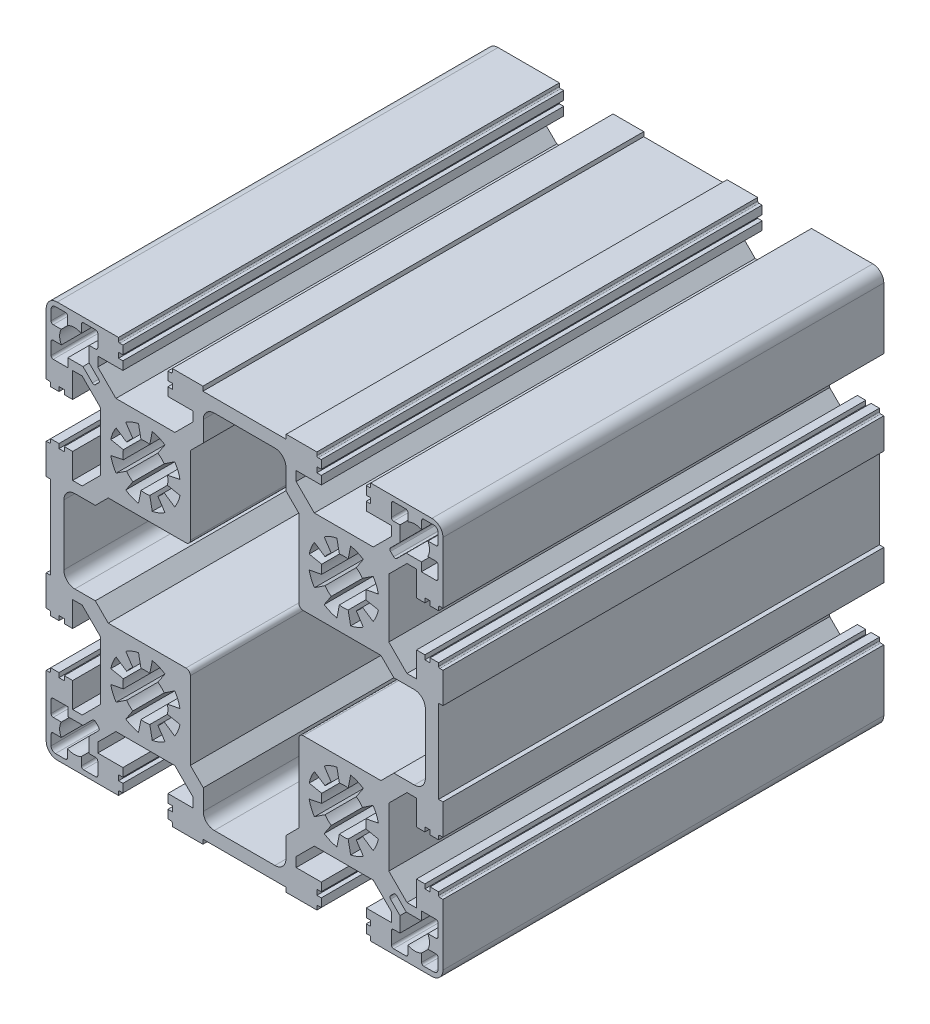
SolidWorks part; units mm, degrees
ref_plane "前视基准面" through (0, 0, 0) normal (0, 0, 1) x (1, 0, 0)
ref_plane "上视基准面" through (0, 0, 0) normal (0, 1, 0) x (1, 0, 0)
ref_plane "右视基准面" through (0, 0, 0) normal (1, 0, 0) x (0, 0, -1)
sketch "草图1" plane through (0, 0, 0) normal (0, 0, 1) x (1, 0, 0)
  line L0 (-27.5688, 44.5458) -> (-41.4688, 44.5458)
  line L1 (-43.9688, 42.0458) -> (-43.9688, 28.1458)
  line L2 (-26.5688, 38.5458) -> (-32.2688, 38.5458)
  line L3 (-37.9688, 32.8458) -> (-37.9688, 27.1458)
  line L4 (-26.5688, 43.5458) -> (-27.2688, 43.5458)
  line L5 (-27.5688, 43.8458) -> (-27.5688, 44.5458)
  line L6 (-43.9688, 28.1458) -> (-43.2688, 28.1458)
  line L7 (-42.9688, 27.8458) -> (-42.9688, 27.1458)
  line L8 (-37.9688, 32.8458) -> (-35.8043, 32.8458)
  line L9 (-41.0688, 28.1458) -> (-39.8688, 28.1458)
  line L10 (-42.9688, 27.1458) -> (-41.0688, 27.1458)
  line L11 (-39.8688, 27.1458) -> (-37.9688, 27.1458)
  line L12 (-32.2688, 38.5458) -> (-32.2688, 36.3813)
  line L13 (-27.5688, 41.6458) -> (-27.5688, 40.4458)
  line L14 (-26.5688, 43.5458) -> (-26.5688, 41.6458)
  line L15 (-26.5688, 40.4458) -> (-26.5688, 38.5458)
  line L16 (-26.5688, 40.4458) -> (-27.5688, 40.4458)
  line L17 (-26.5688, 41.6458) -> (-27.5688, 41.6458)
  line L19 (-39.8688, 27.1458) -> (-39.8688, 28.1458)
  line L20 (-41.0688, 27.1458) -> (-41.0688, 28.1458)
  line L21 (-16.3688, 38.5458) -> (-10.6688, 38.5458)
  line L22 (-16.3688, 43.5458) -> (-15.6688, 43.5458)
  line L23 (-15.3688, 43.8458) -> (-15.3688, 44.5458)
  line L24 (-10.6688, 38.5458) -> (-10.6688, 36.3813)
  line L25 (-15.3688, 41.6458) -> (-15.3688, 40.4458)
  line L26 (-16.3688, 40.4458) -> (-15.3688, 40.4458)
  line L27 (-16.3688, 41.6458) -> (-15.3688, 41.6458)
  line L28 (-16.3688, 43.5458) -> (-16.3688, 41.6458)
  line L29 (-16.3688, 40.4458) -> (-16.3688, 38.5458)
  line L30 (-37.9688, 11.2458) -> (-37.9688, 16.9458)
  line L31 (-43.9688, 15.9458) -> (-43.2688, 15.9458)
  line L32 (-42.9688, 16.2458) -> (-42.9688, 16.9458)
  line L33 (-37.9688, 11.2458) -> (-35.8043, 11.2458)
  line L34 (-41.0688, 15.9458) -> (-39.8688, 15.9458)
  line L35 (-42.9688, 16.9458) -> (-41.0688, 16.9458)
  line L36 (-39.8688, 16.9458) -> (-37.9688, 16.9458)
  line L38 (-39.8688, 16.9458) -> (-39.8688, 15.9458)
  line L39 (-41.0688, 16.9458) -> (-41.0688, 15.9458)
  line L40 (-31.6888, 28.7303) -> (-31.6888, 15.3613)
  line L41 (-14.7843, 32.2658) -> (-28.1532, 32.2658)
  line L42 (-25.9133, 15.394) -> (-24.3022, 17.8053)
  line L43 (-23.0295, 14.1995) -> (-22.4637, 17.0438)
  line L44 (-19.9081, 14.1995) -> (-20.4738, 17.0438)
  line L45 (-17.0242, 15.394) -> (-18.6354, 17.8053)
  line L46 (-14.817, 17.6012) -> (-17.2283, 19.2124)
  line L47 (-13.6225, 20.4851) -> (-16.4668, 21.0508)
  line L48 (-13.6225, 23.6065) -> (-16.4668, 23.0408)
  line L49 (-14.817, 26.4904) -> (-17.2283, 24.8792)
  line L50 (-17.0242, 28.6975) -> (-18.6354, 26.2863)
  line L51 (-19.9081, 29.8921) -> (-20.4738, 27.0478)
  line L52 (-23.0295, 29.8921) -> (-22.4637, 27.0478)
  line L53 (-25.9133, 28.6975) -> (-24.3022, 26.2863)
  line L54 (-28.1205, 26.4904) -> (-25.7093, 24.8792)
  line L55 (-29.3151, 23.6065) -> (-26.4708, 23.0408)
  line L56 (-29.3151, 20.4851) -> (-26.4708, 21.0508)
  line L57 (-28.1205, 17.6012) -> (-25.7093, 19.2124)
  line L58 (-32.2688, 36.3813) -> (-28.1532, 32.2658)
  line L59 (-35.8043, 32.8458) -> (-31.6888, 28.7303)
  line L60 (-10.6688, 36.3813) -> (-14.7843, 32.2658)
  line L61 (-35.8043, 11.2458) -> (-31.6888, 15.3613)
  line L63 (-42.8688, 42.4458) -> (-42.8688, 40.1458)
  line L64 (-42.3688, 39.6458) -> (-40.5642, 39.6458)
  line L65 (-34.2188, 39.6458) -> (-32.7688, 39.6458)
  line L66 (-32.2688, 40.1458) -> (-32.2688, 42.9458)
  line L67 (-32.7688, 43.4458) -> (-35.5088, 43.4458)
  line L68 (-36.0088, 42.9458) -> (-36.0088, 41.1104)
  line L70 (-39.1288, 41.1104) -> (-39.1288, 42.9458)
  line L71 (-39.6288, 43.4458) -> (-41.8688, 43.4458)
  line L72 (-34.2188, 36.21) -> (-34.2188, 39.6458)
  line L73 (-35.633, 34.7958) -> (-33.4896, 32.6524)
  line L74 (-34.2188, 36.21) -> (-32.0754, 34.0666)
  line L75 (-32.7825, 32.6524) -> (-32.0754, 33.3595)
  line L76 (-35.633, 34.7958) -> (-39.0688, 34.7958)
  line L77 (-40.5334, 36.5858) -> (-42.3688, 36.5858)
  line L79 (-42.8688, 36.0858) -> (-42.8688, 33.3458)
  line L80 (-42.3688, 32.8458) -> (-39.0688, 32.8458)
  line L81 (-39.0688, 34.7958) -> (-39.0688, 32.8458)
  line L99 (18.4312, 38.5458) -> (12.7312, 38.5458)
  line L100 (18.4312, 43.5458) -> (17.7312, 43.5458)
  line L101 (17.4312, 43.8458) -> (17.4312, 44.5458)
  line L102 (12.7312, 38.5458) -> (12.7312, 36.3813)
  line L103 (17.4312, 41.6458) -> (17.4312, 40.4458)
  line L104 (18.4312, 43.5458) -> (18.4312, 41.6458)
  line L105 (18.4312, 40.4458) -> (18.4312, 38.5458)
  line L106 (18.4312, 40.4458) -> (17.4312, 40.4458)
  line L107 (18.4312, 41.6458) -> (17.4312, 41.6458)
  line L108 (29.6312, 44.5458) -> (43.5312, 44.5458)
  line L109 (46.0312, 42.0458) -> (46.0312, 28.1458)
  line L110 (28.6312, 38.5458) -> (34.3312, 38.5458)
  line L111 (40.0312, 32.8458) -> (40.0312, 27.1458)
  line L112 (28.6312, 43.5458) -> (29.3312, 43.5458)
  line L113 (29.6312, 43.8458) -> (29.6312, 44.5458)
  line L114 (46.0312, 28.1458) -> (45.3312, 28.1458)
  line L115 (45.0312, 27.8458) -> (45.0312, 27.1458)
  line L116 (40.0312, 32.8458) -> (37.8668, 32.8458)
  line L117 (43.1312, 28.1458) -> (41.9312, 28.1458)
  line L118 (45.0312, 27.1458) -> (43.1312, 27.1458)
  line L119 (41.9312, 27.1458) -> (40.0312, 27.1458)
  line L120 (34.3312, 38.5458) -> (34.3312, 36.3813)
  line L121 (29.6312, 41.6458) -> (29.6312, 40.4458)
  line L122 (28.6312, 40.4458) -> (29.6312, 40.4458)
  line L123 (28.6312, 41.6458) -> (29.6312, 41.6458)
  line L125 (41.9312, 27.1458) -> (41.9312, 28.1458)
  line L126 (43.1312, 27.1458) -> (43.1312, 28.1458)
  line L127 (28.6312, 43.5458) -> (28.6312, 41.6458)
  line L128 (28.6312, 40.4458) -> (28.6312, 38.5458)
  line L129 (40.0312, 11.2458) -> (40.0312, 16.9458)
  line L130 (46.0312, 15.9458) -> (45.3312, 15.9458)
  line L131 (45.0312, 16.2458) -> (45.0312, 16.9458)
  line L132 (40.0312, 11.2458) -> (37.8668, 11.2458)
  line L133 (43.1312, 15.9458) -> (41.9312, 15.9458)
  line L134 (45.0312, 16.9458) -> (43.1312, 16.9458)
  line L135 (41.9312, 16.9458) -> (40.0312, 16.9458)
  line L137 (41.9312, 16.9458) -> (41.9312, 15.9458)
  line L138 (43.1312, 16.9458) -> (43.1312, 15.9458)
  line L139 (33.7512, 15.3613) -> (33.7512, 28.7303)
  line L140 (30.2157, 32.2658) -> (16.8468, 32.2658)
  line L141 (19.0867, 15.394) -> (20.6978, 17.8053)
  line L142 (21.9705, 14.1995) -> (22.5363, 17.0438)
  line L143 (25.0919, 14.1995) -> (24.5262, 17.0438)
  line L144 (27.9758, 15.394) -> (26.3646, 17.8053)
  line L145 (30.183, 17.6012) -> (27.7717, 19.2124)
  line L146 (31.3775, 20.4851) -> (28.5332, 21.0508)
  line L147 (31.3775, 23.6065) -> (28.5332, 23.0408)
  line L148 (30.183, 26.4904) -> (27.7717, 24.8792)
  line L149 (27.9758, 28.6975) -> (26.3646, 26.2863)
  line L150 (25.0919, 29.8921) -> (24.5262, 27.0478)
  line L151 (21.9705, 29.8921) -> (22.5363, 27.0478)
  line L152 (19.0867, 28.6975) -> (20.6978, 26.2863)
  line L153 (16.8795, 26.4904) -> (19.2907, 24.8792)
  line L154 (15.6849, 23.6065) -> (18.5292, 23.0408)
  line L155 (15.6849, 20.4851) -> (18.5292, 21.0508)
  line L156 (16.8795, 17.6012) -> (19.2907, 19.2124)
  line L157 (12.7312, 36.3813) -> (16.8468, 32.2658)
  line L158 (34.3312, 36.3813) -> (30.2157, 32.2658)
  line L159 (37.8668, 32.8458) -> (33.7512, 28.7303)
  line L160 (37.8668, 11.2458) -> (33.7512, 15.3613)
  line L161 (36.2812, 39.6458) -> (34.8312, 39.6458)
  line L162 (34.3312, 40.1458) -> (34.3312, 42.9458)
  line L163 (34.8312, 43.4458) -> (37.5712, 43.4458)
  line L164 (38.0712, 42.9458) -> (38.0712, 41.1104)
  line L165 (41.1912, 41.1104) -> (41.1912, 42.9458)
  line L166 (41.6912, 43.4458) -> (43.9312, 43.4458)
  line L167 (44.9312, 42.4458) -> (44.9312, 40.1458)
  line L168 (44.4312, 39.6458) -> (42.6266, 39.6458)
  line L169 (42.5958, 36.5858) -> (44.4312, 36.5858)
  line L170 (44.9312, 36.0858) -> (44.9312, 33.3458)
  line L171 (44.4312, 32.8458) -> (41.1312, 32.8458)
  line L172 (41.1312, 32.8458) -> (41.1312, 34.7958)
  line L173 (41.1312, 34.7958) -> (37.6954, 34.7958)
  line L174 (37.6954, 34.7958) -> (35.552, 32.6524)
  line L175 (34.8449, 32.6524) -> (34.1378, 33.3595)
  line L176 (34.1378, 34.0666) -> (36.2812, 36.21)
  line L177 (36.2812, 36.21) -> (36.2812, 39.6458)
  line L178 (-15.3688, 44.5458) -> (-8.4188, 44.5458)
  line L179 (-8.4188, 43.5458) -> (10.4812, 43.5458)
  line L180 (-8.3394, 33.4074) -> (-8.3394, 38.0458)
  line L181 (-5.8394, 40.5458) -> (7.9019, 40.5458)
  line L182 (10.4019, 38.0458) -> (10.4019, 33.4074)
  line L183 (-8.3394, 33.4074) -> (-11.2688, 30.478)
  line L184 (17.4312, 44.5458) -> (10.4812, 44.5458)
  line L185 (10.4019, 33.4074) -> (13.3312, 30.478)
  line L186 (10.4812, 43.5458) -> (10.4812, 44.5458)
  line L187 (-8.4188, 43.5458) -> (-8.4188, 44.5458)
  line L188 (-11.2688, 30.478) -> (-11.2688, 12.8458)
  line L189 (13.3312, 30.478) -> (13.3312, 12.8458)
  line L190 (-27.5688, -45.4542) -> (-41.4688, -45.4542)
  line L191 (-43.9688, -42.9542) -> (-43.9688, -29.0542)
  line L192 (-26.5688, -39.4542) -> (-32.2688, -39.4542)
  line L193 (-37.9688, -33.7542) -> (-37.9688, -28.0542)
  line L194 (-26.5688, -44.4542) -> (-27.2688, -44.4542)
  line L195 (-27.5688, -44.7542) -> (-27.5688, -45.4542)
  line L196 (-43.9688, -29.0542) -> (-43.2688, -29.0542)
  line L197 (-42.9688, -28.7542) -> (-42.9688, -28.0542)
  line L198 (-37.9688, -33.7542) -> (-35.8043, -33.7542)
  line L199 (-41.0688, -29.0542) -> (-39.8688, -29.0542)
  line L200 (-42.9688, -28.0542) -> (-41.0688, -28.0542)
  line L201 (-39.8688, -28.0542) -> (-37.9688, -28.0542)
  line L202 (-32.2688, -39.4542) -> (-32.2688, -37.2897)
  line L203 (-27.5688, -42.5542) -> (-27.5688, -41.3542)
  line L204 (-26.5688, -44.4542) -> (-26.5688, -42.5542)
  line L205 (-26.5688, -41.3542) -> (-26.5688, -39.4542)
  line L206 (-26.5688, -41.3542) -> (-27.5688, -41.3542)
  line L207 (-26.5688, -42.5542) -> (-27.5688, -42.5542)
  line L209 (-39.8688, -28.0542) -> (-39.8688, -29.0542)
  line L210 (-41.0688, -28.0542) -> (-41.0688, -29.0542)
  line L211 (-16.3688, -39.4542) -> (-10.6688, -39.4542)
  line L212 (-16.3688, -44.4542) -> (-15.6688, -44.4542)
  line L213 (-15.3688, -44.7542) -> (-15.3688, -45.4542)
  line L214 (-10.6688, -39.4542) -> (-10.6688, -37.2897)
  line L215 (-15.3688, -42.5542) -> (-15.3688, -41.3542)
  line L216 (-16.3688, -41.3542) -> (-15.3688, -41.3542)
  line L217 (-16.3688, -42.5542) -> (-15.3688, -42.5542)
  line L218 (-16.3688, -44.4542) -> (-16.3688, -42.5542)
  line L219 (-16.3688, -41.3542) -> (-16.3688, -39.4542)
  line L220 (-37.9688, -12.1542) -> (-37.9688, -17.8542)
  line L221 (-43.9688, -16.8542) -> (-43.2688, -16.8542)
  line L222 (-42.9688, -17.1542) -> (-42.9688, -17.8542)
  line L223 (-37.9688, -12.1542) -> (-35.8043, -12.1542)
  line L224 (-41.0688, -16.8542) -> (-39.8688, -16.8542)
  line L225 (-42.9688, -17.8542) -> (-41.0688, -17.8542)
  line L226 (-39.8688, -17.8542) -> (-37.9688, -17.8542)
  line L228 (-39.8688, -17.8542) -> (-39.8688, -16.8542)
  line L229 (-41.0688, -17.8542) -> (-41.0688, -16.8542)
  line L230 (-31.6888, -29.6387) -> (-31.6888, -16.2697)
  line L231 (-14.7843, -33.1742) -> (-28.1532, -33.1742)
  line L232 (-25.9133, -16.3025) -> (-24.3022, -18.7137)
  line L233 (-23.0295, -15.1079) -> (-22.4637, -17.9522)
  line L234 (-19.9081, -15.1079) -> (-20.4738, -17.9522)
  line L235 (-17.0242, -16.3025) -> (-18.6354, -18.7137)
  line L236 (-14.817, -18.5096) -> (-17.2283, -20.1208)
  line L237 (-13.6225, -21.3935) -> (-16.4668, -21.9592)
  line L238 (-13.6225, -24.5149) -> (-16.4668, -23.9492)
  line L239 (-14.817, -27.3988) -> (-17.2283, -25.7876)
  line L240 (-17.0242, -29.606) -> (-18.6354, -27.1947)
  line L241 (-19.9081, -30.8005) -> (-20.4738, -27.9562)
  line L242 (-23.0295, -30.8005) -> (-22.4637, -27.9562)
  line L243 (-25.9133, -29.606) -> (-24.3022, -27.1947)
  line L244 (-28.1205, -27.3988) -> (-25.7093, -25.7876)
  line L245 (-29.3151, -24.5149) -> (-26.4708, -23.9492)
  line L246 (-29.3151, -21.3935) -> (-26.4708, -21.9592)
  line L247 (-28.1205, -18.5096) -> (-25.7093, -20.1208)
  line L248 (-32.2688, -37.2897) -> (-28.1532, -33.1742)
  line L249 (-35.8043, -33.7542) -> (-31.6888, -29.6387)
  line L250 (-10.6688, -37.2897) -> (-14.7843, -33.1742)
  line L251 (-35.8043, -12.1542) -> (-31.6888, -16.2697)
  line L253 (-42.8688, -43.3542) -> (-42.8688, -41.0542)
  line L254 (-42.3688, -40.5542) -> (-40.5642, -40.5542)
  line L255 (-34.2188, -40.5542) -> (-32.7688, -40.5542)
  line L256 (-32.2688, -41.0542) -> (-32.2688, -43.8542)
  line L257 (-32.7688, -44.3542) -> (-35.5088, -44.3542)
  line L258 (-36.0088, -43.8542) -> (-36.0088, -42.0188)
  line L260 (-39.1288, -42.0188) -> (-39.1288, -43.8542)
  line L261 (-39.6288, -44.3542) -> (-41.8688, -44.3542)
  line L262 (-34.2188, -37.1184) -> (-34.2188, -40.5542)
  line L263 (-35.633, -35.7042) -> (-33.4896, -33.5608)
  line L264 (-34.2188, -37.1184) -> (-32.0754, -34.975)
  line L265 (-32.7825, -33.5608) -> (-32.0754, -34.2679)
  line L266 (-35.633, -35.7042) -> (-39.0688, -35.7042)
  line L267 (-40.5334, -37.4942) -> (-42.3688, -37.4942)
  line L269 (-42.8688, -36.9942) -> (-42.8688, -34.2542)
  line L270 (-42.3688, -33.7542) -> (-39.0688, -33.7542)
  line L271 (-39.0688, -35.7042) -> (-39.0688, -33.7542)
  line L289 (18.4312, -39.4542) -> (12.7312, -39.4542)
  line L290 (18.4312, -44.4542) -> (17.7312, -44.4542)
  line L291 (17.4312, -44.7542) -> (17.4312, -45.4542)
  line L292 (12.7312, -39.4542) -> (12.7312, -37.2897)
  line L293 (17.4312, -42.5542) -> (17.4312, -41.3542)
  line L294 (18.4312, -44.4542) -> (18.4312, -42.5542)
  line L295 (18.4312, -41.3542) -> (18.4312, -39.4542)
  line L296 (18.4312, -41.3542) -> (17.4312, -41.3542)
  line L297 (18.4312, -42.5542) -> (17.4312, -42.5542)
  line L298 (29.6312, -45.4542) -> (43.5312, -45.4542)
  line L299 (46.0312, -42.9542) -> (46.0312, -29.0542)
  line L300 (28.6312, -39.4542) -> (34.3312, -39.4542)
  line L301 (40.0312, -33.7542) -> (40.0312, -28.0542)
  line L302 (28.6312, -44.4542) -> (29.3312, -44.4542)
  line L303 (29.6312, -44.7542) -> (29.6312, -45.4542)
  line L304 (46.0312, -29.0542) -> (45.3312, -29.0542)
  line L305 (45.0312, -28.7542) -> (45.0312, -28.0542)
  line L306 (40.0312, -33.7542) -> (37.8668, -33.7542)
  line L307 (43.1312, -29.0542) -> (41.9312, -29.0542)
  line L308 (45.0312, -28.0542) -> (43.1312, -28.0542)
  line L309 (41.9312, -28.0542) -> (40.0312, -28.0542)
  line L310 (34.3312, -39.4542) -> (34.3312, -37.2897)
  line L311 (29.6312, -42.5542) -> (29.6312, -41.3542)
  line L312 (28.6312, -41.3542) -> (29.6312, -41.3542)
  line L313 (28.6312, -42.5542) -> (29.6312, -42.5542)
  line L315 (41.9312, -28.0542) -> (41.9312, -29.0542)
  line L316 (43.1312, -28.0542) -> (43.1312, -29.0542)
  line L317 (28.6312, -44.4542) -> (28.6312, -42.5542)
  line L318 (28.6312, -41.3542) -> (28.6312, -39.4542)
  line L319 (40.0312, -12.1542) -> (40.0312, -17.8542)
  line L320 (46.0312, -16.8542) -> (45.3312, -16.8542)
  line L321 (45.0312, -17.1542) -> (45.0312, -17.8542)
  line L322 (40.0312, -12.1542) -> (37.8668, -12.1542)
  line L323 (43.1312, -16.8542) -> (41.9312, -16.8542)
  line L324 (45.0312, -17.8542) -> (43.1312, -17.8542)
  line L325 (41.9312, -17.8542) -> (40.0312, -17.8542)
  line L327 (41.9312, -17.8542) -> (41.9312, -16.8542)
  line L328 (43.1312, -17.8542) -> (43.1312, -16.8542)
  line L329 (33.7512, -16.2697) -> (33.7512, -29.6387)
  line L330 (30.2157, -33.1742) -> (16.8468, -33.1742)
  line L331 (19.0867, -16.3025) -> (20.6978, -18.7137)
  line L332 (21.9705, -15.1079) -> (22.5363, -17.9522)
  line L333 (25.0919, -15.1079) -> (24.5262, -17.9522)
  line L334 (27.9758, -16.3025) -> (26.3646, -18.7137)
  line L335 (30.183, -18.5096) -> (27.7717, -20.1208)
  line L336 (31.3775, -21.3935) -> (28.5332, -21.9592)
  line L337 (31.3775, -24.5149) -> (28.5332, -23.9492)
  line L338 (30.183, -27.3988) -> (27.7717, -25.7876)
  line L339 (27.9758, -29.606) -> (26.3646, -27.1947)
  line L340 (25.0919, -30.8005) -> (24.5262, -27.9562)
  line L341 (21.9705, -30.8005) -> (22.5363, -27.9562)
  line L342 (19.0867, -29.606) -> (20.6978, -27.1947)
  line L343 (16.8795, -27.3988) -> (19.2907, -25.7876)
  line L344 (15.6849, -24.5149) -> (18.5292, -23.9492)
  line L345 (15.6849, -21.3935) -> (18.5292, -21.9592)
  line L346 (16.8795, -18.5096) -> (19.2907, -20.1208)
  line L347 (12.7312, -37.2897) -> (16.8468, -33.1742)
  line L348 (34.3312, -37.2897) -> (30.2157, -33.1742)
  line L349 (37.8668, -33.7542) -> (33.7512, -29.6387)
  line L350 (37.8668, -12.1542) -> (33.7512, -16.2697)
  line L351 (36.2812, -40.5542) -> (34.8312, -40.5542)
  line L352 (34.3312, -41.0542) -> (34.3312, -43.8542)
  line L353 (34.8312, -44.3542) -> (37.5712, -44.3542)
  line L354 (38.0712, -43.8542) -> (38.0712, -42.0188)
  line L355 (41.1912, -42.0188) -> (41.1912, -43.8542)
  line L356 (41.6912, -44.3542) -> (43.9312, -44.3542)
  line L357 (44.9312, -43.3542) -> (44.9312, -41.0542)
  line L358 (44.4312, -40.5542) -> (42.6266, -40.5542)
  line L359 (42.5958, -37.4942) -> (44.4312, -37.4942)
  line L360 (44.9312, -36.9942) -> (44.9312, -34.2542)
  line L361 (44.4312, -33.7542) -> (41.1312, -33.7542)
  line L362 (41.1312, -33.7542) -> (41.1312, -35.7042)
  line L363 (41.1312, -35.7042) -> (37.6954, -35.7042)
  line L364 (37.6954, -35.7042) -> (35.552, -33.5608)
  line L365 (34.8449, -33.5608) -> (34.1378, -34.2679)
  line L366 (34.1378, -34.975) -> (36.2812, -37.1184)
  line L367 (36.2812, -37.1184) -> (36.2812, -40.5542)
  line L368 (-15.3688, -45.4542) -> (-8.4188, -45.4542)
  line L369 (-8.4188, -44.4542) -> (10.4812, -44.4542)
  line L370 (-8.3394, -34.3158) -> (-8.3394, -38.9542)
  line L371 (-5.8394, -41.4542) -> (7.9019, -41.4542)
  line L372 (10.4019, -38.9542) -> (10.4019, -34.3158)
  line L373 (-8.3394, -34.3158) -> (-11.2688, -31.3864)
  line L374 (17.4312, -45.4542) -> (10.4812, -45.4542)
  line L375 (10.4019, -34.3158) -> (13.3312, -31.3864)
  line L376 (10.4812, -44.4542) -> (10.4812, -45.4542)
  line L377 (-8.4188, -44.4542) -> (-8.4188, -45.4542)
  line L378 (-11.2688, -31.3864) -> (-11.2688, -13.7542)
  line L379 (13.3312, -31.3864) -> (13.3312, -13.7542)
  line L380 (-32.8304, 8.9164) -> (-37.4688, 8.9164)
  line L381 (-39.9688, 6.4164) -> (-39.9688, -7.3248)
  line L382 (-37.4688, -9.8248) -> (-32.8304, -9.8248)
  line L383 (-32.8304, 8.9164) -> (-29.901, 11.8458)
  line L384 (-32.8304, -9.8248) -> (-29.901, -12.7542)
  line L385 (-29.901, 11.8458) -> (-12.2688, 11.8458)
  line L386 (-29.901, -12.7542) -> (-12.2688, -12.7542)
  line L387 (-43.9688, 15.9458) -> (-43.9688, 8.9958)
  line L388 (-42.9688, 8.9958) -> (-42.9688, -9.9042)
  line L389 (-43.9688, -16.8542) -> (-43.9688, -9.9042)
  line L390 (-42.9688, -9.9042) -> (-43.9688, -9.9042)
  line L391 (-42.9688, 8.9958) -> (-43.9688, 8.9958)
  line L392 (34.8928, 8.9164) -> (39.5312, 8.9164)
  line L393 (42.0312, 6.4164) -> (42.0312, -7.3248)
  line L394 (39.5312, -9.8248) -> (34.8928, -9.8248)
  line L395 (34.8928, 8.9164) -> (31.9635, 11.8458)
  line L396 (34.8928, -9.8248) -> (31.9635, -12.7542)
  line L397 (31.9635, 11.8458) -> (14.3312, 11.8458)
  line L398 (31.9635, -12.7542) -> (14.3312, -12.7542)
  line L399 (46.0312, 15.9458) -> (46.0312, 8.9958)
  line L400 (45.0312, 8.9958) -> (45.0312, -9.9042)
  line L401 (46.0312, -16.8542) -> (46.0312, -9.9042)
  line L402 (45.0312, -9.9042) -> (46.0312, -9.9042)
  line L403 (45.0312, 8.9958) -> (46.0312, 8.9958)
  arc A0 (-41.4688, 44.5458) -> (-43.9688, 42.0458) centre (-41.4688, 42.0458) ccw
  arc A1 (-27.5688, 43.8458) -> (-27.2688, 43.5458) centre (-27.2688, 43.8458) ccw
  arc A2 (-42.9688, 27.8458) -> (-43.2688, 28.1458) centre (-43.2688, 27.8458) ccw
  arc A3 (-15.6688, 43.5458) -> (-15.3688, 43.8458) centre (-15.6688, 43.8458) ccw
  arc A4 (-43.2688, 15.9458) -> (-42.9688, 16.2458) centre (-43.2688, 16.2458) ccw
  arc A5 (-22.4637, 17.0438) -> (-20.4738, 17.0438) centre (-21.4688, 22.0458) ccw
  arc A6 (-18.6354, 17.8053) -> (-17.2283, 19.2124) centre (-21.4688, 22.0458) ccw
  arc A7 (-16.4668, 21.0508) -> (-16.4668, 23.0408) centre (-21.4688, 22.0458) ccw
  arc A8 (-17.2283, 24.8792) -> (-18.6354, 26.2863) centre (-21.4688, 22.0458) ccw
  arc A9 (-20.4738, 27.0478) -> (-22.4637, 27.0478) centre (-21.4688, 22.0458) ccw
  arc A10 (-24.3022, 26.2863) -> (-25.7093, 24.8792) centre (-21.4688, 22.0458) ccw
  arc A11 (-26.4708, 23.0408) -> (-26.4708, 21.0508) centre (-21.4688, 22.0458) ccw
  arc A12 (-25.7093, 19.2124) -> (-24.3022, 17.8053) centre (-21.4688, 22.0458) ccw
  arc A13 (-25.9133, 15.394) -> (-23.0295, 14.1995) centre (-21.4688, 22.0458) ccw
  arc A14 (-19.9081, 14.1995) -> (-17.0242, 15.394) centre (-21.4688, 22.0458) ccw
  arc A15 (-14.817, 17.6012) -> (-13.6225, 20.4851) centre (-21.4688, 22.0458) ccw
  arc A16 (-13.6225, 23.6065) -> (-14.817, 26.4904) centre (-21.4688, 22.0458) ccw
  arc A17 (-17.0242, 28.6975) -> (-19.9081, 29.8921) centre (-21.4688, 22.0458) ccw
  arc A18 (-23.0295, 29.8921) -> (-25.9133, 28.6975) centre (-21.4688, 22.0458) ccw
  arc A19 (-28.1205, 26.4904) -> (-29.3151, 23.6065) centre (-21.4688, 22.0458) ccw
  arc A20 (-29.3151, 20.4851) -> (-28.1205, 17.6012) centre (-21.4688, 22.0458) ccw
  arc A21 (-40.5642, 39.6458) -> (-40.5334, 36.5858) centre (-37.5688, 38.1458) ccw
  arc A22 (-36.0088, 41.1104) -> (-39.1288, 41.1104) centre (-37.5688, 38.1458) ccw
  arc A23 (-41.8688, 43.4458) -> (-42.8688, 42.4458) centre (-41.8688, 42.4458) ccw
  arc A24 (-42.8688, 40.1458) -> (-42.3688, 39.6458) centre (-42.3688, 40.1458) ccw
  arc A25 (-32.7688, 39.6458) -> (-32.2688, 40.1458) centre (-32.7688, 40.1458) ccw
  arc A26 (-32.2688, 42.9458) -> (-32.7688, 43.4458) centre (-32.7688, 42.9458) ccw
  arc A27 (-35.5088, 43.4458) -> (-36.0088, 42.9458) centre (-35.5088, 42.9458) ccw
  arc A28 (-39.1288, 42.9458) -> (-39.6288, 43.4458) centre (-39.6288, 42.9458) ccw
  arc A29 (-33.4896, 32.6524) -> (-32.7825, 32.6524) centre (-33.136, 33.0059) ccw
  arc A30 (-32.0754, 33.3595) -> (-32.0754, 34.0666) centre (-32.4289, 33.7131) ccw
  arc A31 (-42.3688, 36.5858) -> (-42.8688, 36.0858) centre (-42.3688, 36.0858) ccw
  arc A32 (-42.8688, 33.3458) -> (-42.3688, 32.8458) centre (-42.3688, 33.3458) ccw
  arc A45 (17.4312, 43.8458) -> (17.7312, 43.5458) centre (17.7312, 43.8458) ccw
  arc A46 (46.0312, 42.0458) -> (43.5312, 44.5458) centre (43.5312, 42.0458) ccw
  arc A47 (29.3312, 43.5458) -> (29.6312, 43.8458) centre (29.3312, 43.8458) ccw
  arc A48 (45.3312, 28.1458) -> (45.0312, 27.8458) centre (45.3312, 27.8458) ccw
  arc A49 (45.0312, 16.2458) -> (45.3312, 15.9458) centre (45.3312, 16.2458) ccw
  arc A50 (22.5363, 17.0438) -> (24.5262, 17.0438) centre (23.5312, 22.0458) ccw
  arc A51 (26.3646, 17.8053) -> (27.7717, 19.2124) centre (23.5312, 22.0458) ccw
  arc A52 (28.5332, 21.0508) -> (28.5332, 23.0408) centre (23.5312, 22.0458) ccw
  arc A53 (27.7717, 24.8792) -> (26.3646, 26.2863) centre (23.5312, 22.0458) ccw
  arc A54 (24.5262, 27.0478) -> (22.5363, 27.0478) centre (23.5312, 22.0458) ccw
  arc A55 (20.6978, 26.2863) -> (19.2907, 24.8792) centre (23.5312, 22.0458) ccw
  arc A56 (18.5292, 23.0408) -> (18.5292, 21.0508) centre (23.5312, 22.0458) ccw
  arc A57 (19.2907, 19.2124) -> (20.6978, 17.8053) centre (23.5312, 22.0458) ccw
  arc A58 (19.0867, 15.394) -> (21.9705, 14.1995) centre (23.5312, 22.0458) ccw
  arc A59 (25.0919, 14.1995) -> (27.9758, 15.394) centre (23.5312, 22.0458) ccw
  arc A60 (30.183, 17.6012) -> (31.3775, 20.4851) centre (23.5312, 22.0458) ccw
  arc A61 (31.3775, 23.6065) -> (30.183, 26.4904) centre (23.5312, 22.0458) ccw
  arc A62 (27.9758, 28.6975) -> (25.0919, 29.8921) centre (23.5312, 22.0458) ccw
  arc A63 (21.9705, 29.8921) -> (19.0867, 28.6975) centre (23.5312, 22.0458) ccw
  arc A64 (16.8795, 26.4904) -> (15.6849, 23.6065) centre (23.5312, 22.0458) ccw
  arc A65 (15.6849, 20.4851) -> (16.8795, 17.6012) centre (23.5312, 22.0458) ccw
  arc A66 (34.3312, 40.1458) -> (34.8312, 39.6458) centre (34.8312, 40.1458) ccw
  arc A67 (34.8312, 43.4458) -> (34.3312, 42.9458) centre (34.8312, 42.9458) ccw
  arc A68 (38.0712, 42.9458) -> (37.5712, 43.4458) centre (37.5712, 42.9458) ccw
  arc A69 (41.1912, 41.1104) -> (38.0712, 41.1104) centre (39.6312, 38.1458) ccw
  arc A70 (41.6912, 43.4458) -> (41.1912, 42.9458) centre (41.6912, 42.9458) ccw
  arc A71 (44.9312, 42.4458) -> (43.9312, 43.4458) centre (43.9312, 42.4458) ccw
  arc A72 (44.4312, 39.6458) -> (44.9312, 40.1458) centre (44.4312, 40.1458) ccw
  arc A73 (42.5958, 36.5858) -> (42.6266, 39.6458) centre (39.6312, 38.1458) ccw
  arc A74 (44.9312, 36.0858) -> (44.4312, 36.5858) centre (44.4312, 36.0858) ccw
  arc A75 (44.4312, 32.8458) -> (44.9312, 33.3458) centre (44.4312, 33.3458) ccw
  arc A76 (34.8449, 32.6524) -> (35.552, 32.6524) centre (35.1985, 33.0059) ccw
  arc A77 (34.1378, 34.0666) -> (34.1378, 33.3595) centre (34.4914, 33.7131) ccw
  arc A78 (-5.8394, 40.5458) -> (-8.3394, 38.0458) centre (-5.8394, 38.0458) ccw
  arc A79 (10.4019, 38.0458) -> (7.9019, 40.5458) centre (7.9019, 38.0458) ccw
  arc A80 (13.3312, 12.8458) -> (14.3312, 11.8458) centre (14.3312, 12.8458) ccw
  arc A81 (-43.9688, -42.9542) -> (-41.4688, -45.4542) centre (-41.4688, -42.9542) ccw
  arc A82 (-27.2688, -44.4542) -> (-27.5688, -44.7542) centre (-27.2688, -44.7542) ccw
  arc A83 (-43.2688, -29.0542) -> (-42.9688, -28.7542) centre (-43.2688, -28.7542) ccw
  arc A84 (-15.3688, -44.7542) -> (-15.6688, -44.4542) centre (-15.6688, -44.7542) ccw
  arc A85 (-42.9688, -17.1542) -> (-43.2688, -16.8542) centre (-43.2688, -17.1542) ccw
  arc A86 (-20.4738, -17.9522) -> (-22.4637, -17.9522) centre (-21.4688, -22.9542) ccw
  arc A87 (-17.2283, -20.1208) -> (-18.6354, -18.7137) centre (-21.4688, -22.9542) ccw
  arc A88 (-16.4668, -23.9492) -> (-16.4668, -21.9592) centre (-21.4688, -22.9542) ccw
  arc A89 (-18.6354, -27.1947) -> (-17.2283, -25.7876) centre (-21.4688, -22.9542) ccw
  arc A90 (-22.4637, -27.9562) -> (-20.4738, -27.9562) centre (-21.4688, -22.9542) ccw
  arc A91 (-25.7093, -25.7876) -> (-24.3022, -27.1947) centre (-21.4688, -22.9542) ccw
  arc A92 (-26.4708, -21.9592) -> (-26.4708, -23.9492) centre (-21.4688, -22.9542) ccw
  arc A93 (-24.3022, -18.7137) -> (-25.7093, -20.1208) centre (-21.4688, -22.9542) ccw
  arc A94 (-23.0295, -15.1079) -> (-25.9133, -16.3025) centre (-21.4688, -22.9542) ccw
  arc A95 (-17.0242, -16.3025) -> (-19.9081, -15.1079) centre (-21.4688, -22.9542) ccw
  arc A96 (-13.6225, -21.3935) -> (-14.817, -18.5096) centre (-21.4688, -22.9542) ccw
  arc A97 (-14.817, -27.3988) -> (-13.6225, -24.5149) centre (-21.4688, -22.9542) ccw
  arc A98 (-19.9081, -30.8005) -> (-17.0242, -29.606) centre (-21.4688, -22.9542) ccw
  arc A99 (-25.9133, -29.606) -> (-23.0295, -30.8005) centre (-21.4688, -22.9542) ccw
  arc A100 (-29.3151, -24.5149) -> (-28.1205, -27.3988) centre (-21.4688, -22.9542) ccw
  arc A101 (-28.1205, -18.5096) -> (-29.3151, -21.3935) centre (-21.4688, -22.9542) ccw
  arc A102 (-40.5334, -37.4942) -> (-40.5642, -40.5542) centre (-37.5688, -39.0542) ccw
  arc A103 (-39.1288, -42.0188) -> (-36.0088, -42.0188) centre (-37.5688, -39.0542) ccw
  arc A104 (-42.8688, -43.3542) -> (-41.8688, -44.3542) centre (-41.8688, -43.3542) ccw
  arc A105 (-42.3688, -40.5542) -> (-42.8688, -41.0542) centre (-42.3688, -41.0542) ccw
  arc A106 (-32.2688, -41.0542) -> (-32.7688, -40.5542) centre (-32.7688, -41.0542) ccw
  arc A107 (-32.7688, -44.3542) -> (-32.2688, -43.8542) centre (-32.7688, -43.8542) ccw
  arc A108 (-36.0088, -43.8542) -> (-35.5088, -44.3542) centre (-35.5088, -43.8542) ccw
  arc A109 (-39.6288, -44.3542) -> (-39.1288, -43.8542) centre (-39.6288, -43.8542) ccw
  arc A110 (-32.7825, -33.5608) -> (-33.4896, -33.5608) centre (-33.136, -33.9144) ccw
  arc A111 (-32.0754, -34.975) -> (-32.0754, -34.2679) centre (-32.4289, -34.6215) ccw
  arc A112 (-42.8688, -36.9942) -> (-42.3688, -37.4942) centre (-42.3688, -36.9942) ccw
  arc A113 (-42.3688, -33.7542) -> (-42.8688, -34.2542) centre (-42.3688, -34.2542) ccw
  arc A126 (17.7312, -44.4542) -> (17.4312, -44.7542) centre (17.7312, -44.7542) ccw
  arc A127 (43.5312, -45.4542) -> (46.0312, -42.9542) centre (43.5312, -42.9542) ccw
  arc A128 (29.6312, -44.7542) -> (29.3312, -44.4542) centre (29.3312, -44.7542) ccw
  arc A129 (45.0312, -28.7542) -> (45.3312, -29.0542) centre (45.3312, -28.7542) ccw
  arc A130 (45.3312, -16.8542) -> (45.0312, -17.1542) centre (45.3312, -17.1542) ccw
  arc A131 (24.5262, -17.9522) -> (22.5363, -17.9522) centre (23.5312, -22.9542) ccw
  arc A132 (27.7717, -20.1208) -> (26.3646, -18.7137) centre (23.5312, -22.9542) ccw
  arc A133 (28.5332, -23.9492) -> (28.5332, -21.9592) centre (23.5312, -22.9542) ccw
  arc A134 (26.3646, -27.1947) -> (27.7717, -25.7876) centre (23.5312, -22.9542) ccw
  arc A135 (22.5363, -27.9562) -> (24.5262, -27.9562) centre (23.5312, -22.9542) ccw
  arc A136 (19.2907, -25.7876) -> (20.6978, -27.1947) centre (23.5312, -22.9542) ccw
  arc A137 (18.5292, -21.9592) -> (18.5292, -23.9492) centre (23.5312, -22.9542) ccw
  arc A138 (20.6978, -18.7137) -> (19.2907, -20.1208) centre (23.5312, -22.9542) ccw
  arc A139 (21.9705, -15.1079) -> (19.0867, -16.3025) centre (23.5312, -22.9542) ccw
  arc A140 (27.9758, -16.3025) -> (25.0919, -15.1079) centre (23.5312, -22.9542) ccw
  arc A141 (31.3775, -21.3935) -> (30.183, -18.5096) centre (23.5312, -22.9542) ccw
  arc A142 (30.183, -27.3988) -> (31.3775, -24.5149) centre (23.5312, -22.9542) ccw
  arc A143 (25.0919, -30.8005) -> (27.9758, -29.606) centre (23.5312, -22.9542) ccw
  arc A144 (19.0867, -29.606) -> (21.9705, -30.8005) centre (23.5312, -22.9542) ccw
  arc A145 (15.6849, -24.5149) -> (16.8795, -27.3988) centre (23.5312, -22.9542) ccw
  arc A146 (16.8795, -18.5096) -> (15.6849, -21.3935) centre (23.5312, -22.9542) ccw
  arc A147 (34.8312, -40.5542) -> (34.3312, -41.0542) centre (34.8312, -41.0542) ccw
  arc A148 (34.3312, -43.8542) -> (34.8312, -44.3542) centre (34.8312, -43.8542) ccw
  arc A149 (37.5712, -44.3542) -> (38.0712, -43.8542) centre (37.5712, -43.8542) ccw
  arc A150 (38.0712, -42.0188) -> (41.1912, -42.0188) centre (39.6312, -39.0542) ccw
  arc A151 (41.1912, -43.8542) -> (41.6912, -44.3542) centre (41.6912, -43.8542) ccw
  arc A152 (43.9312, -44.3542) -> (44.9312, -43.3542) centre (43.9312, -43.3542) ccw
  arc A153 (44.9312, -41.0542) -> (44.4312, -40.5542) centre (44.4312, -41.0542) ccw
  arc A154 (42.6266, -40.5542) -> (42.5958, -37.4942) centre (39.6312, -39.0542) ccw
  arc A155 (44.4312, -37.4942) -> (44.9312, -36.9942) centre (44.4312, -36.9942) ccw
  arc A156 (44.9312, -34.2542) -> (44.4312, -33.7542) centre (44.4312, -34.2542) ccw
  arc A157 (35.552, -33.5608) -> (34.8449, -33.5608) centre (35.1985, -33.9144) ccw
  arc A158 (34.1378, -34.2679) -> (34.1378, -34.975) centre (34.4914, -34.6215) ccw
  arc A159 (-8.3394, -38.9542) -> (-5.8394, -41.4542) centre (-5.8394, -38.9542) ccw
  arc A160 (7.9019, -41.4542) -> (10.4019, -38.9542) centre (7.9019, -38.9542) ccw
  arc A161 (-11.2688, -13.7542) -> (-12.2688, -12.7542) centre (-12.2688, -13.7542) ccw
  arc A162 (14.3312, -12.7542) -> (13.3312, -13.7542) centre (14.3312, -13.7542) ccw
  arc A163 (-37.4688, 8.9164) -> (-39.9688, 6.4164) centre (-37.4688, 6.4164) ccw
  arc A164 (-39.9688, -7.3248) -> (-37.4688, -9.8248) centre (-37.4688, -7.3248) ccw
  arc A165 (-12.2688, 11.8458) -> (-11.2688, 12.8458) centre (-12.2688, 12.8458) ccw
  arc A166 (42.0312, 6.4164) -> (39.5312, 8.9164) centre (39.5312, 6.4164) ccw
  arc A167 (39.5312, -9.8248) -> (42.0312, -7.3248) centre (39.5312, -7.3248) ccw
extrude "凸台-拉伸1" add sketch "草图1" along normal blind 100
